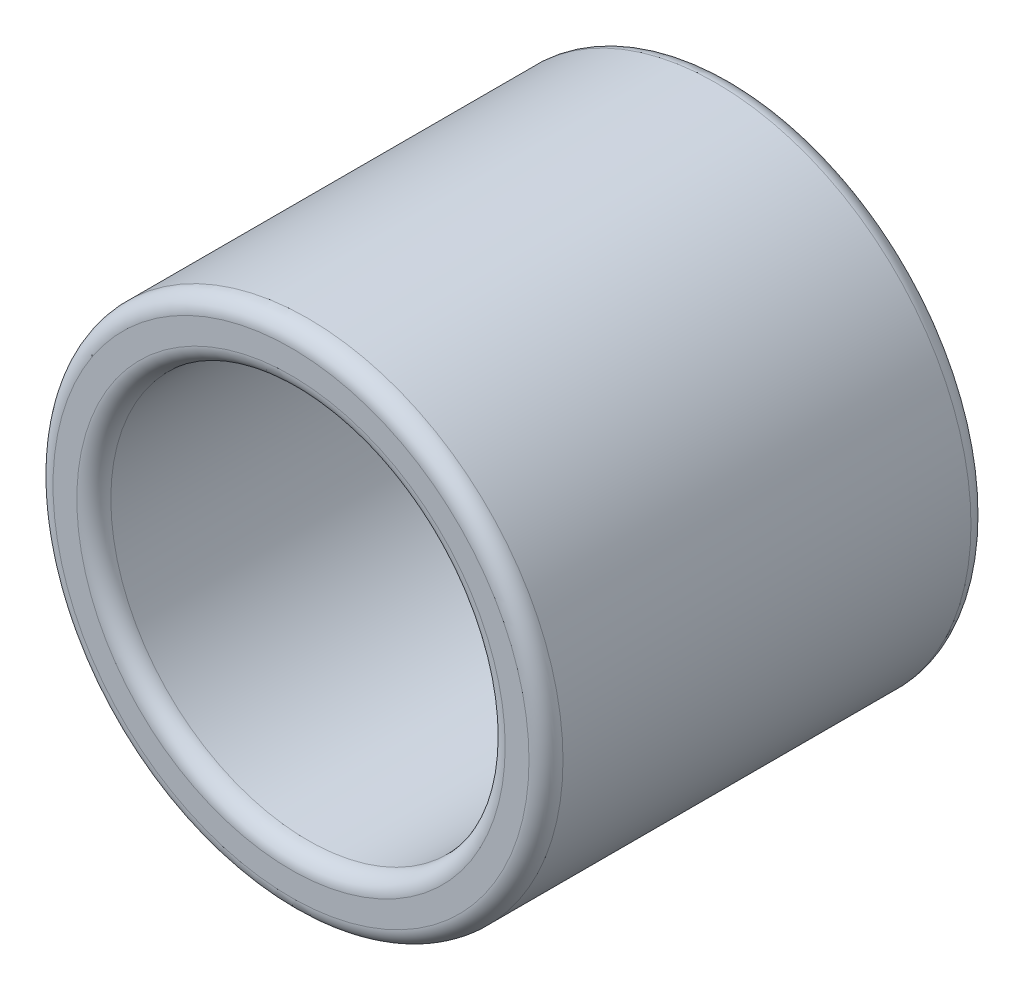
SolidWorks part; units mm, degrees
material "TPU"
ref_plane "Front Plane" through (0, 0, 0) normal (0, 0, 1) x (1, 0, 0)
ref_plane "Top Plane" through (0, 0, 0) normal (0, 1, 0) x (1, 0, 0)
ref_plane "Right Plane" through (0, 0, 0) normal (1, 0, 0) x (0, 0, -1)
sketch "Sketch1" plane through (0, 0, 0) normal (0, 0, 1) x (1, 0, 0)
  circle A0 centre (0, 0) radius 7.5
  dimension "D1" = 15
extrude "Boss-Extrude1" add sketch "Sketch1" along normal blind 13
sketch "Sketch3" plane through (0, 0, 13) normal (0, 0, 1) x (1, 0, 0)
  circle A0 centre (0, 0) radius 5.8
  dimension "D1" = 11.6
extrude "Cut-Extrude1" cut sketch "Sketch3" against normal blind 10
fillet "Fillet1" radius 0.5 4 edges at (7.5, 0, 0) (7.5, 0, 13) (5.8, 0, 13) (5.8, 0, 3)
